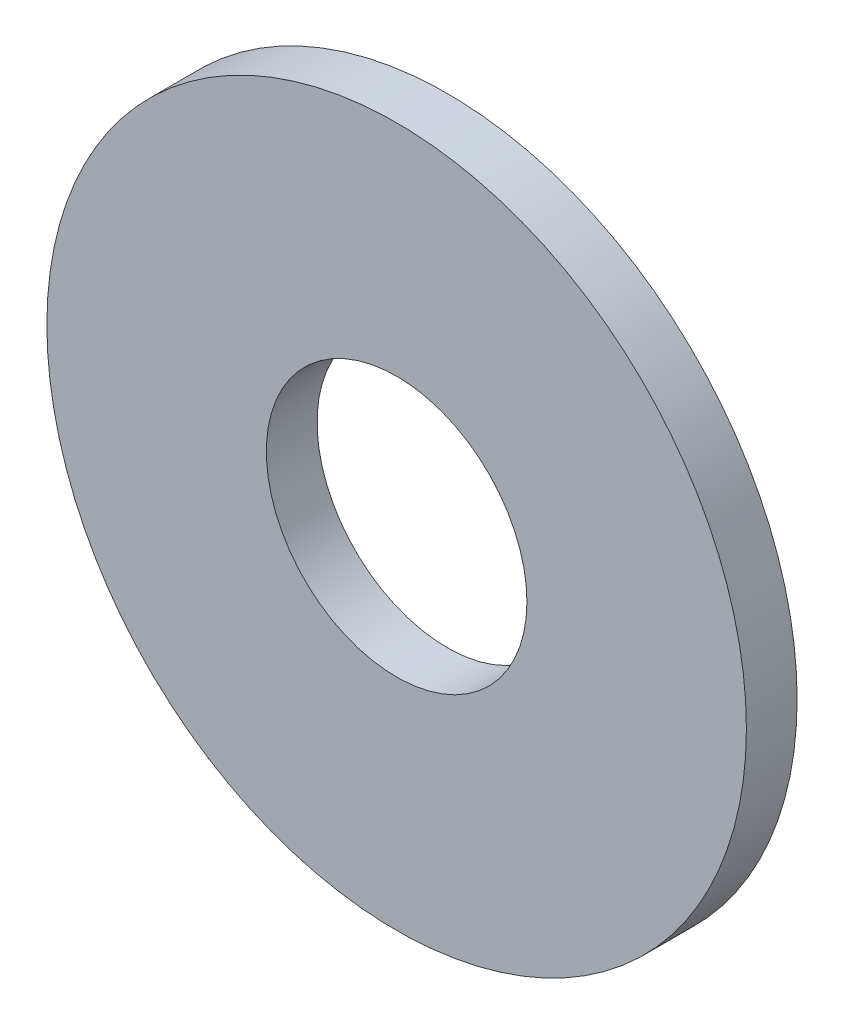
SolidWorks part; units mm, degrees
ref_plane "Front Plane" through (0, 0, 0) normal (0, 0, 1) x (1, 0, 0)
ref_plane "Top Plane" through (0, 0, 0) normal (0, 1, 0) x (1, 0, 0)
ref_plane "Right Plane" through (0, 0, 0) normal (1, 0, 0) x (0, 0, -1)
sketch "Sketch1" plane through (0, 0, 0) normal (0, 0, 1) x (1, 0, 0)
  circle A0 centre (0, 0) radius 20
  circle A1 centre (0, 0) radius 7.45
  dimension "D1" = 40
  dimension "D2" = 14.9
extrude "Boss-Extrude1" add sketch "Sketch1" along normal blind 2.9 contours A0 | A1
